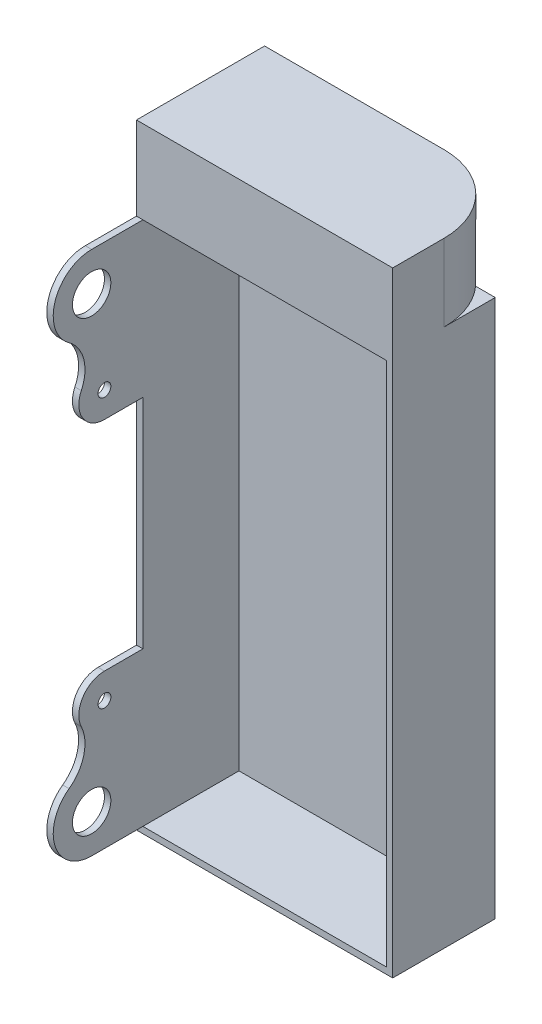
SolidWorks part; units mm, degrees
ref_plane "Front Plane" through (0, 0, 0) normal (0, 0, 1) x (1, 0, 0)
ref_plane "Top Plane" through (0, 0, 0) normal (0, 1, 0) x (1, 0, 0)
ref_plane "Right Plane" through (0, 0, 0) normal (1, 0, 0) x (0, 0, -1)
sketch "Sketch1" plane through (0, 0, 0) normal (0, 0, 1) x (1, 0, 0)
  line L0 (55, 0) -> (-55, 0) construction
  line L1 (-63.5, 133.35) -> (63.5, 133.35)
  line L2 (-63.5, 133.35) -> (-63.5, -133.35)
  line L3 (-63.5, -133.35) -> (63.5, -133.35)
  line L4 (63.5, 133.35) -> (63.5, -133.35)
  line L5 (0, -55) -> (0, 55) construction
  dimension "D1" = 127
  dimension "D2" = 266.7
  dimension "D3" = 133.35
  dimension "D4" = 63.5
extrude "Boss-Extrude1" add sketch "Sketch1" along normal mid plane 50.8
shell "Shell1" thickness 3.175
sketch "Sketch2" plane through (-63.5, 0, 0) normal (-1, 0, 0) x (0, 0, 1)
  line L0 (50.8, 130.175) -> (25.4, 130.175)
  line L1 (44.45, 53.975) -> (25.4, 53.975)
  line L2 (25.4, 133.35) -> (25.4, -133.35) construction
  line L3 (25.4, 130.175) -> (25.4, 53.975)
  line L5 (25.4, 133.35) -> (-25.4, 133.35) construction
  arc A0 (61.9722, 95.695) -> (50.8, 130.175) centre (50.8, 111.125) ccw
  arc A1 (44.45, 53.975) -> (55.9278, 72.111) centre (44.45, 66.675) ccw
  arc A2 (61.9722, 95.695) -> (55.9278, 72.111) centre (73.1445, 80.2651) ccw
  circle A3 centre (50.8, 111.125) radius 9.525
  circle A4 centre (44.45, 66.675) radius 3.175
  dimension "D2" = 12.7
  dimension "D3" = 19.05
  dimension "D4" = 19.05
  dimension "D7" = 19.05
  dimension "D8" = 6.35
  dimension "D1" = 76.2
  dimension "D5" = 25.4
  dimension "D6" = 19.05
  dimension "D9" = 3.175
extrude "Boss-Extrude2" add sketch "Sketch2" against normal up to surface (3.175 mm away) up to face at (-60.325, 0, 1.5875)
sketch "Sketch3" plane through (0, 133.35, 0) normal (0, 1, 0) x (1, 0, 0)
  line L0 (63.5, -25.4) -> (-63.5, -25.4)
  line L1 (-63.5, -25.4) -> (-63.5, 25.4) construction
  line L2 (-63.5, -25.4) -> (-63.5, 38.1)
  line L3 (-63.5, 38.1) -> (25.4, 38.1)
  line L4 (63.5, -25.4) -> (63.5, 0)
  line L5 (63.5, -25.4) -> (63.5, 25.4) construction
  arc A1 (25.4, 38.1) -> (63.5, 0) centre (25.4, 0) cw
  dimension "D1" = 25.4
  dimension "D2" = 63.5
extrude "Boss-Extrude3" add sketch "Sketch3" along normal blind 38.1
mirror "Mirror1" about plane through (0, 0, 0) normal (0, 1, 0) of "Boss-Extrude2"
equation "\"D3@Sketch1\"=\"D2@Sketch1\"/2"
equation "\"D4@Sketch1\"=\"D1@Sketch1\"/2"
